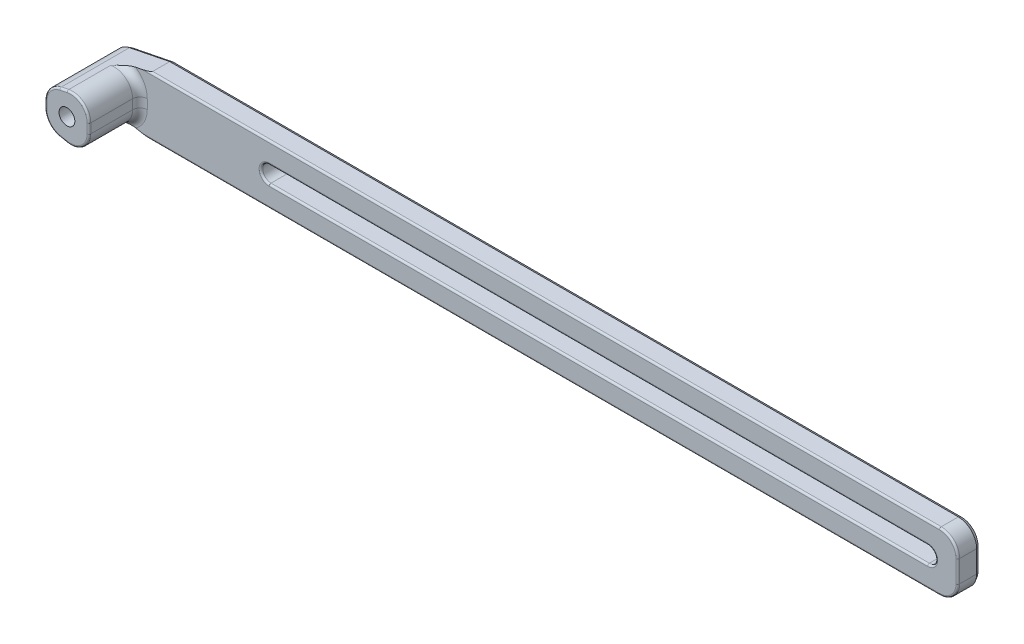
SolidWorks part; units mm, degrees
ref_plane "Front Plane" through (0, 0, 0) normal (0, 0, 1) x (1, 0, 0)
ref_plane "Top Plane" through (0, 0, 0) normal (0, 1, 0) x (1, 0, 0)
ref_plane "Right Plane" through (0, 0, 0) normal (1, 0, 0) x (0, 0, -1)
sketch "Sketch1" plane through (0, 0, 0) normal (0, 0, 1) x (1, 0, 0)
  line L0 (101.75, 0) -> (-77.75, 0) construction
  line L1 (-110, -8) -> (110, -8)
  line L2 (-110, -8) -> (-110, 8)
  line L3 (-110, 8) -> (110, 8)
  line L4 (110, -8) -> (110, 8)
  line L5 (-110, -8) -> (110, 8) construction
  line L6 (-110, 8) -> (110, -8) construction
  line L7 (101.75, -2.25) -> (-77.75, -2.25)
  line L8 (101.75, 2.25) -> (-77.75, 2.25)
  line L9 (-110, 8) -> (-125, 5)
  line L10 (-125, 5) -> (-125, -5)
  line L11 (-125, -5) -> (-110, -8)
  arc A0 (101.75, -2.25) -> (101.75, 2.25) centre (101.75, 0) ccw
  arc A1 (-77.75, 2.25) -> (-77.75, -2.25) centre (-77.75, 0) ccw
  circle A2 centre (-119, 0) radius 2.15
  point P0 (0, 0)
  point P8 (12, 0)
  point P13 (104, 0)
  point P14 (-80, 0)
  point P15 (-110, 0)
  point P18 (-125, 0)
  dimension "D8" = 4.3
  dimension "D1" = 6
  dimension "D2" = 4.5
  dimension "D3" = 16
  dimension "D4" = 220
  dimension "D5" = 30
  dimension "D6" = 10
  dimension "D7" = 15
  dimension "D9" = 6
extrude "Boss-Extrude1" add sketch "Sketch1" along normal blind 6 contours L1 L4 L3 L2 A1 L8 A0 L7 | L10 L11 L2 L9
sketch "Sketch3" plane through (0, 0, 6) normal (0, 0, 1) x (1, 0, 0)
  line L0 (-125, 5) -> (-125, -5)
  line L1 (-125, -5) -> (-113, -7.4)
  line L2 (-125, -5) -> (-110, -8) construction
  line L3 (-113, -7.4) -> (-113, 7.4)
  line L4 (-110, 8) -> (-125, 5) construction
  line L5 (-113, 7.4) -> (-125, 5)
  circle A0 centre (-119, 0) radius 2.15 construction
  circle A1 centre (-119, 0) radius 2.15
  dimension "D1" = 12
extrude "Boss-Extrude2" add sketch "Sketch3" along normal blind 13.9
fillet "Fillet1" radius 5 2 edges at (110, -8, 3) (110, 8, 3)
fillet "Fillet2" radius 5 4 edges at (-113, -7.4, 12.95) (-113, 7.4, 12.95) (-125, -5, 9.95) (-125, 5, 9.95)
chamfer "Chamfer1" distance 0.5 angle 60 14 edges at (-115.4903, -6.9019, 0) (-2.5, -8, 0) (-123.8667, -4.0709, 0) (108.5355, -6.5355, 0) (-125, 0, 0) (110, 0, 0) (-123.8667, 4.0709, 0) (108.5355, 6.5355, 0) (-115.4903, 6.9019, 0) (-2.5, 8, 0) (12, -2.25, 0) (104, 0, 0) (-80, 0, 0) (12, 2.25, 0)
fillet "Fillet3" radius 0.5 9 edges at (104, 0, 6) (12, -2.25, 6) (-80, 0, 6) (-2.5, -8, 6) (108.5355, -6.5355, 6) (110, 0, 6) (108.5355, 6.5355, 6) (12, 2.25, 6) (-2.5, 8, 6)
fillet "Fillet4" radius 2 3 edges at (-114.8301, -5.1677, 6) (-113, 0, 6) (-114.8301, 5.1677, 6)
fillet "Fillet5" radius 0.5 8 edges at (-113, 0, 19.9) (-114.8301, -5.1677, 19.9) (-119.9806, -6.0039, 19.9) (-123.8667, -4.0709, 19.9) (-125, 0, 19.9) (-123.8667, 4.0709, 19.9) (-119.9806, 6.0039, 19.9) (-114.8301, 5.1677, 19.9)
